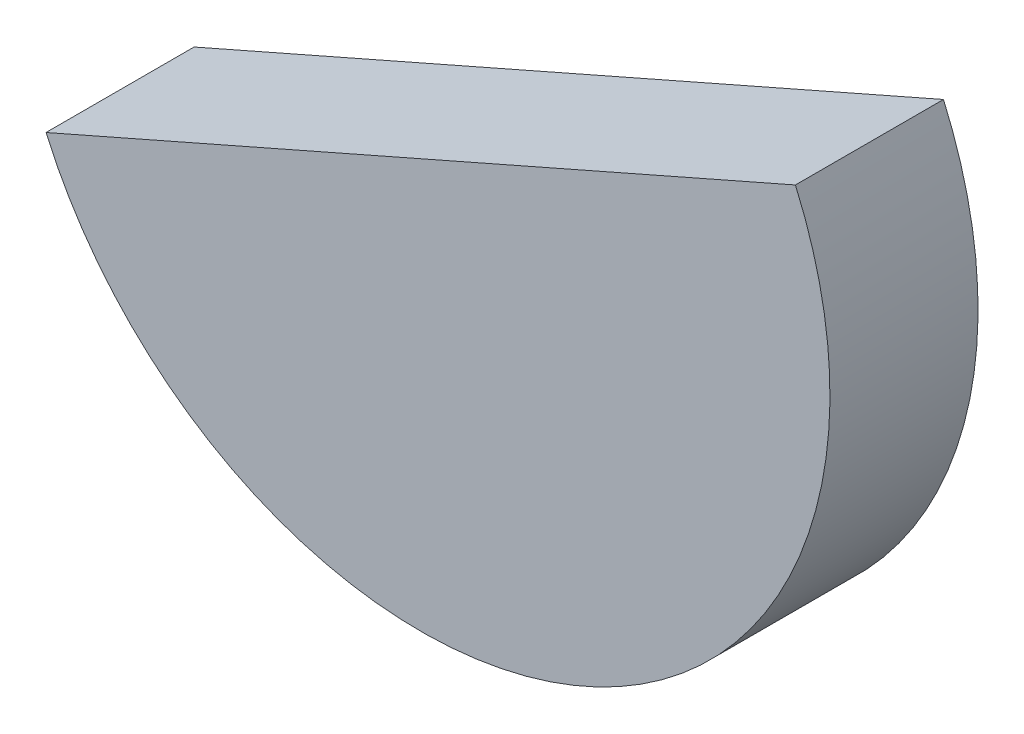
SolidWorks part; units mm, degrees
ref_plane "Front Plane" through (0, 0, 0) normal (0, 0, 1) x (1, 0, 0)
ref_plane "Top Plane" through (0, 0, 0) normal (0, 1, 0) x (1, 0, 0)
ref_plane "Right Plane" through (0, 0, 0) normal (1, 0, 0) x (0, 0, -1)
sketch "CurveSketch" plane through (0, 0, 0) normal (0, 0, 1) x (1, 0, 0)
  line L0 (-23.2013, 5.7822) -> (12.9273, 21.6558)
  arc A0 (12.9273, 21.6558) -> (-23.2013, 5.7822) centre (-5.137, 13.719) cw
  dimension "D1" = 19.731
extrude "CurveBoss" add sketch "CurveSketch" along normal blind 7.139
